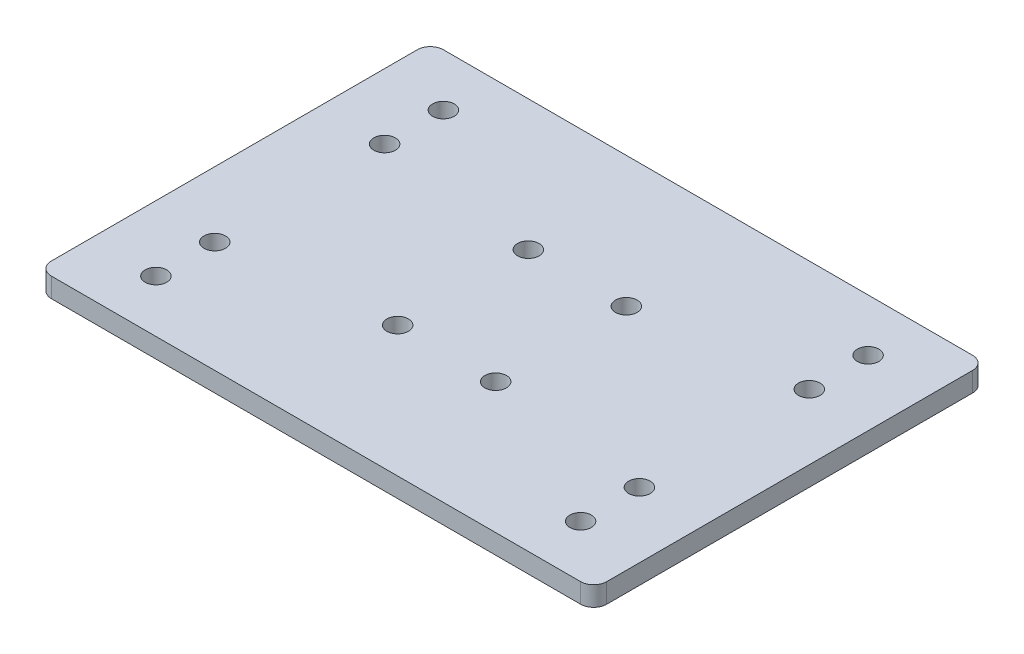
SolidWorks part; units mm, degrees
ref_plane "前视基准面" through (0, 0, 0) normal (0, 0, 1) x (1, 0, 0)
ref_plane "上视基准面" through (0, 0, 0) normal (0, 1, 0) x (1, 0, 0)
ref_plane "右视基准面" through (0, 0, 0) normal (1, 0, 0) x (0, 0, -1)
sketch "草图1" plane through (0, 0, 0) normal (0, 1, 0) x (1, 0, 0)
  line L1 (-42.5, -30) -> (42.5, -30)
  line L2 (-42.5, -30) -> (-42.5, 30)
  line L3 (-42.5, 30) -> (42.5, 30)
  line L4 (42.5, -30) -> (42.5, 30)
  line L5 (-42.5, -30) -> (42.5, 30) construction
  line L6 (-42.5, 30) -> (42.5, -30) construction
  point P0 (0, 0)
  dimension "D1" = 60
  dimension "D2" = 85
extrude "凸台-拉伸1" add sketch "草图1" along normal blind 3
sketch "草图2" plane through (0, 3, 0) normal (0, 1, 0) x (1, 0, 0)
  line L5 (-7.5, -10) -> (7.5, -10) construction
  line L6 (-7.5, -10) -> (-7.5, 10) construction
  line L7 (-7.5, 10) -> (7.5, 10) construction
  line L8 (7.5, -10) -> (7.5, 10) construction
  line L9 (-7.5, -10) -> (7.5, 10) construction
  line L10 (-7.5, 10) -> (7.5, -10) construction
  circle A0 centre (7.5, 10) radius 1.65
  circle A1 centre (-7.5, 10) radius 1.65
  circle A2 centre (-7.5, -10) radius 1.65
  circle A3 centre (7.5, -10) radius 1.65
  point P0 (0, 0)
  dimension "D3" = 3.3
  dimension "D4" = 3.3
  dimension "D5" = 3.3
  dimension "D6" = 3.3
  dimension "D1" = 20
  dimension "D2" = 15
extrude "切除-拉伸1" cut sketch "草图2" against normal blind 3
sketch "草图3" plane through (0, 3, 0) normal (0, 1, 0) x (1, 0, 0)
  line L0 (32.5, 52.6896) -> (32.5, -64.7084) construction
  line L1 (42.5, -30) -> (42.5, 30) construction
  line L2 (-67.1887, 0) -> (70.564, 0) construction
  circle A0 centre (32.5, 13) radius 1.65
  circle A1 centre (32.5, 22) radius 1.65
  circle A2 centre (32.5, -13) radius 1.65
  circle A3 centre (32.5, -22) radius 1.65
  dimension "D2" = 3.3
  dimension "D3" = 3.3
  dimension "D1" = 10
  dimension "D4" = 9
  dimension "D5" = 22
extrude "切除-拉伸2" cut sketch "草图3" against normal blind 100 contours A1
mirror "镜向1" about plane through (0, 0, 0) normal (1, 0, 0) of "切除-拉伸2"
fillet "圆角1" radius 2 4 edges at (42.5, 1.5, 30) (-42.5, 1.5, 30) (-42.5, 1.5, -30) (42.5, 1.5, -30)
